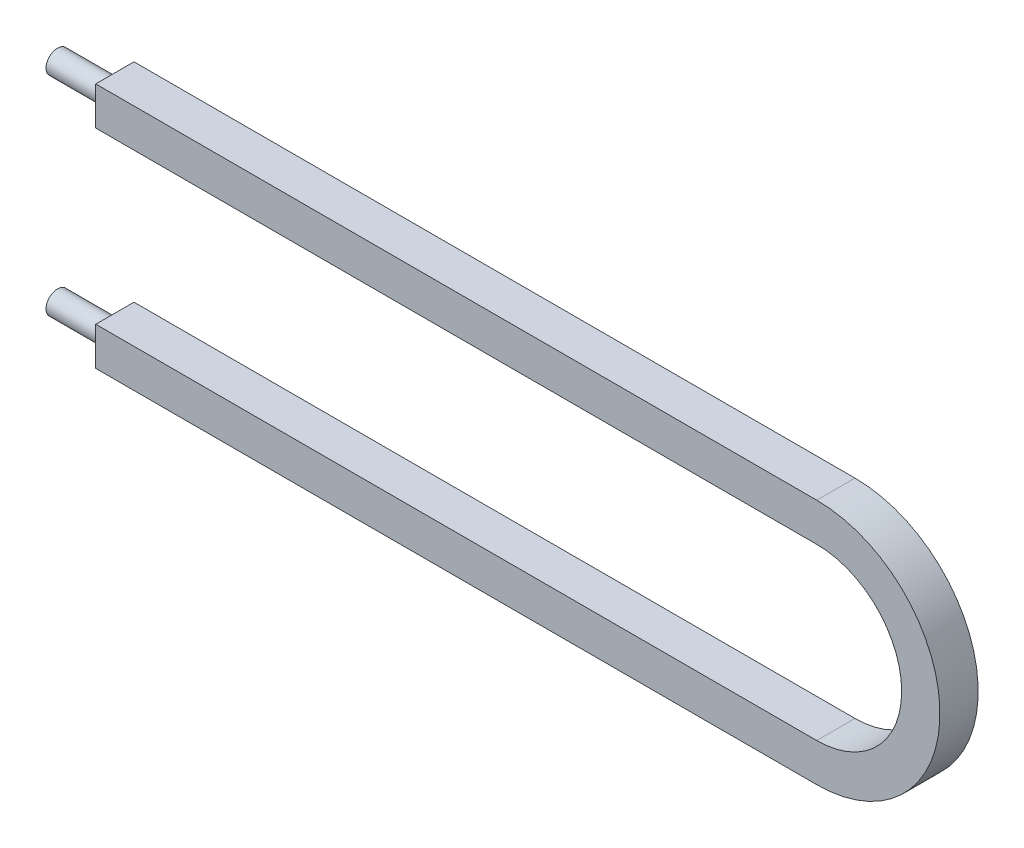
SolidWorks part; units mm, degrees
ref_plane "Alzado" through (0, 0, 0) normal (0, 0, 1) x (1, 0, 0)
ref_plane "Planta" through (0, 0, 0) normal (0, 1, 0) x (1, 0, 0)
ref_plane "Vista lateral" through (0, 0, 0) normal (1, 0, 0) x (0, 0, -1)
sketch "Sketch1" plane through (0, 0, 0) normal (0, 0, 1) x (1, 0, 0)
  line L0 (0, 0) -> (188.4679, 0)
  line L1 (188.4679, -64.4097) -> (0, -64.4097)
  line L2 (0, -10) -> (188.4679, -10)
  line L3 (188.4679, -54.4097) -> (0, -54.4097)
  line L4 (0, -10) -> (0, 0)
  line L5 (0, -54.4097) -> (0, -64.4097)
  arc A0 (188.4679, 0) -> (188.4679, -64.4097) centre (188.4679, -32.2048) cw
  arc A1 (188.4679, -10) -> (188.4679, -54.4097) centre (188.4679, -32.2048) cw
  point P8 (220.6728, -32.2048)
  dimension "D1" = 32.2048
  dimension "D3" = 10
  dimension "D2" = 188.4679
extrude "Boss-Extrude1" add sketch "Sketch1" along normal blind 10
sketch "Sketch2" plane through (0, 0, 0) normal (-1, 0, 0) x (0, 0, 1)
  line L0 (5, 0) -> (5, -10) construction
  line L1 (10, 0) -> (0, 0) construction
  line L2 (10, -10) -> (0, -10) construction
  circle A0 centre (5, -4.907) radius 3
  dimension "D1" = 6
extrude "Boss-Extrude2" add sketch "Sketch2" along normal blind 15
sketch "Sketch3" plane through (0, 0, 0) normal (-1, 0, 0) x (0, 0, 1)
  line L0 (5, -54.4097) -> (5, -64.4097) construction
  line L1 (10, -54.4097) -> (0, -54.4097) construction
  line L2 (10, -64.4097) -> (0, -64.4097) construction
  circle A0 centre (5, -59.4097) radius 3
  dimension "D1" = 6
extrude "Boss-Extrude3" add sketch "Sketch3" along normal blind 15
